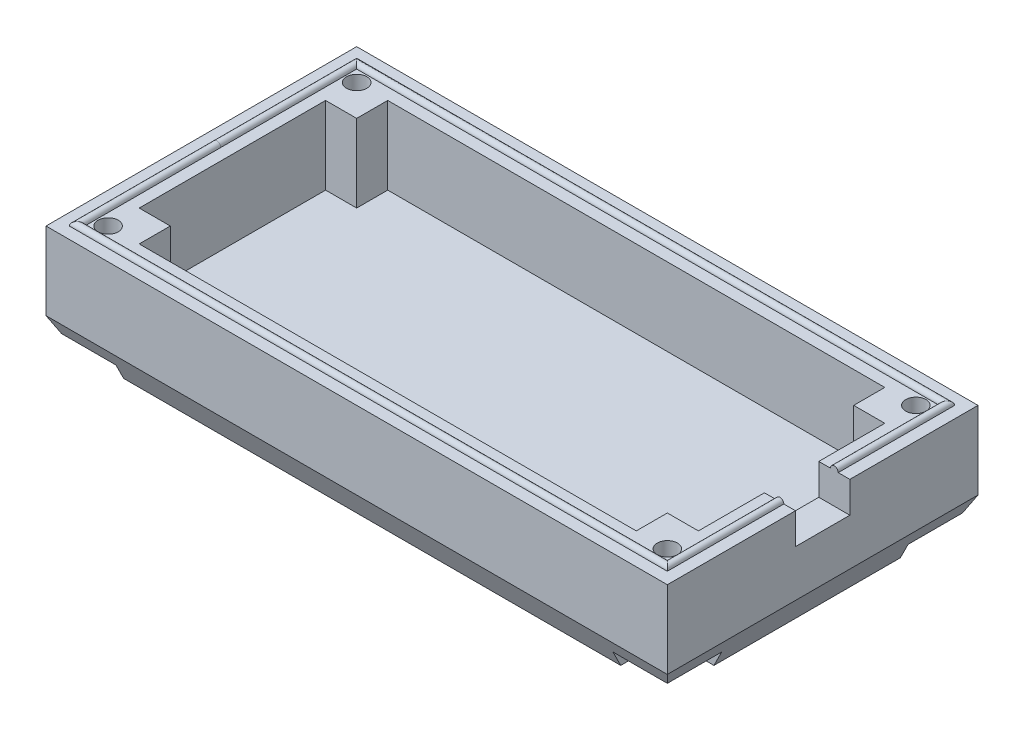
SolidWorks part; units mm, degrees
ref_plane "Piano frontale" through (0, 0, 0) normal (0, 0, 1) x (1, 0, 0)
ref_plane "Piano superiore" through (0, 0, 0) normal (0, 1, 0) x (1, 0, 0)
ref_plane "Piano destro" through (0, 0, 0) normal (1, 0, 0) x (0, 0, -1)
sketch "Schizzo2" plane through (0, 0, 0) normal (0, 1, 0) x (1, 0, 0)
  line L1 (20, -10) -> (-20, -10)
  line L2 (20, -10) -> (20, 10)
  line L3 (20, 10) -> (-20, 10)
  line L4 (-20, -10) -> (-20, 10)
  line L5 (20, -10) -> (-20, 10) construction
  line L6 (20, 10) -> (-20, -10) construction
  point P0 (0, 0)
  dimension "D1" = 40
  dimension "D2" = 20
extrude "Estrusione-Estrusione1" add sketch "Schizzo2" against normal blind 7
sketch "Schizzo3" plane through (0, 0, 0) normal (0, 1, 0) x (1, 0, 0)
  line L0 (20, 10) -> (-20, 10) construction
  line L1 (-16, 8) -> (16, 8)
  line L2 (-18, 6) -> (-18, -6)
  line L3 (-16, -8) -> (16, -8)
  line L4 (18, 6) -> (18, -6)
  line L5 (-16, 7.1111) -> (16, -7.1111) construction
  line L6 (-16, -7.1111) -> (16, 7.1111) construction
  line L7 (-18, 6) -> (-16, 6)
  line L8 (-20, 10) -> (-20, -10) construction
  line L9 (-16, 6) -> (-16, 8)
  line L10 (16, -8) -> (16, -6)
  line L11 (16, -6) -> (18, -6)
  line L12 (18, 6) -> (16, 6)
  line L13 (16, 6) -> (16, 8)
  line L14 (-16, -8) -> (-16, -6)
  line L15 (-16, -6) -> (-18, -6)
  point P0 (0, 0)
  dimension "D1" = 2
  dimension "D2" = 2
  dimension "D3" = 2
extrude "Taglio-Estrusione1" cut sketch "Schizzo3" against normal blind 5
sketch "Schizzo4" plane through (0, 0, 0) normal (0, 0, 1) x (1, 0, 0)
  line L0 (-20, 0) -> (20, 0) construction
  line L1 (-18.75, 0) -> (-19.25, 0)
  arc A0 (-18.75, 0) -> (-19.25, 0) centre (-19, 0) ccw
  dimension "D2" = 0.5
  dimension "D1" = 1
sketch "Schizzo5" plane through (0, 0, 0) normal (0, 1, 0) x (1, 0, 0)
  line L0 (-20, 10) -> (-20, -10) construction
  line L1 (19, -9) -> (-19, -9)
  line L2 (19, -9) -> (19, 9)
  line L3 (19, 9) -> (-19, 9)
  line L4 (-19, -9) -> (-19, 9)
  line L5 (19, -9) -> (-19, 9) construction
  line L6 (19, 9) -> (-19, -9) construction
  line L7 (20, 10) -> (-20, 10) construction
  point P0 (0, 0)
  dimension "D1" = 1
  dimension "D2" = 1
sweep "Sweep1" add profiles "Schizzo4" path "Schizzo5"
chamfer "Smusso1" distance 1 distance2 2 4 edges at (0, -7, 10) (20, -7, 0) (0, -7, -10) (-20, -7, 0)
sketch "Schizzo6" plane through (0, -7, 0) normal (0, -1, 0) x (1, 0, 0)
  line L1 (-20, 10) -> (-16, 10)
  line L2 (-20, 10) -> (-20, 6)
  line L3 (-20, 6) -> (-16, 6)
  line L4 (-16, 10) -> (-16, 6)
  line L5 (20, 10) -> (16, 10)
  line L6 (20, 10) -> (20, 6)
  line L7 (20, 6) -> (16, 6)
  line L8 (16, 10) -> (16, 6)
  line L9 (20, -10) -> (16, -10)
  line L10 (20, -10) -> (20, -6)
  line L11 (20, -6) -> (16, -6)
  line L12 (16, -10) -> (16, -6)
  line L13 (-20, -10) -> (-16, -10)
  line L14 (-20, -10) -> (-20, -6)
  line L15 (-20, -6) -> (-16, -6)
  line L16 (-16, -10) -> (-16, -6)
  dimension "D1" = 4
extrude "Taglio-Estrusione2" cut sketch "Schizzo6" against normal blind 1
hole_wizard "Foro per Vite M1-1" positions "Schizzo12" profile "Schizzo13" hole size "M1" standard "ISO" end condition through all
sketch "Schizzo12" plane through (0, -6, 0) normal (0, -1, 0) x (-1, 0, 0)
  line L0 (-20, -10) -> (-20, 10) construction
  line L1 (-19, 6) -> (-16, 6) construction
  point P0 (-18, 8)
  dimension "D1" = 2
  dimension "D2" = 2
sketch "Schizzo13" plane through (18, -6, -8) normal (1, 0, 0) x (0, 0, -1)
  line L0 (0, 0) -> (0, 6.25)
  line L1 (0, 6.25) -> (0.65, 6.25)
  line L2 (0.65, 6.25) -> (0.65, 0.025)
  line L3 (0.65, 0.025) -> (0.675, 0)
  line L5 (0.675, 0) -> (0, 0)
  line L6 (-0.65, 0.025) -> (-0.675, 0) construction
  line L11 (0, -6.35) -> (0, 107.95) construction
  dimension "Thru Hole Dia." = 1.3
  dimension "Thru Hole Depth" = 6.25
  dimension "Near C'Sink Dia." = 1.35
  dimension "Near C'Sink Angle" = 90
mirror "Specchia1" about plane through (0, 0, 0) normal (1, 0, 0) of "Foro per Vite M1-1"
mirror "Specchia2" about plane through (0, 0, 0) normal (0, 0, 1) of "Specchia1", "Foro per Vite M1-1"
sketch "Schizzo14" plane through (20, 0, 0) normal (1, 0, 0) x (0, 0, -1)
  line L1 (-1.75, 2) -> (1.75, 2)
  line L2 (-1.75, 2) -> (-1.75, -2)
  line L3 (-1.75, -2) -> (1.75, -2)
  line L4 (1.75, 2) -> (1.75, -2)
  line L5 (-1.75, 2) -> (1.75, -2) construction
  line L6 (-1.75, -2) -> (1.75, 2) construction
  point P0 (0, 0)
  dimension "D1" = 2
  dimension "D2" = 3.5
extrude "Taglio-Estrusione3" cut sketch "Schizzo14" against normal blind 3 and the other way through all
